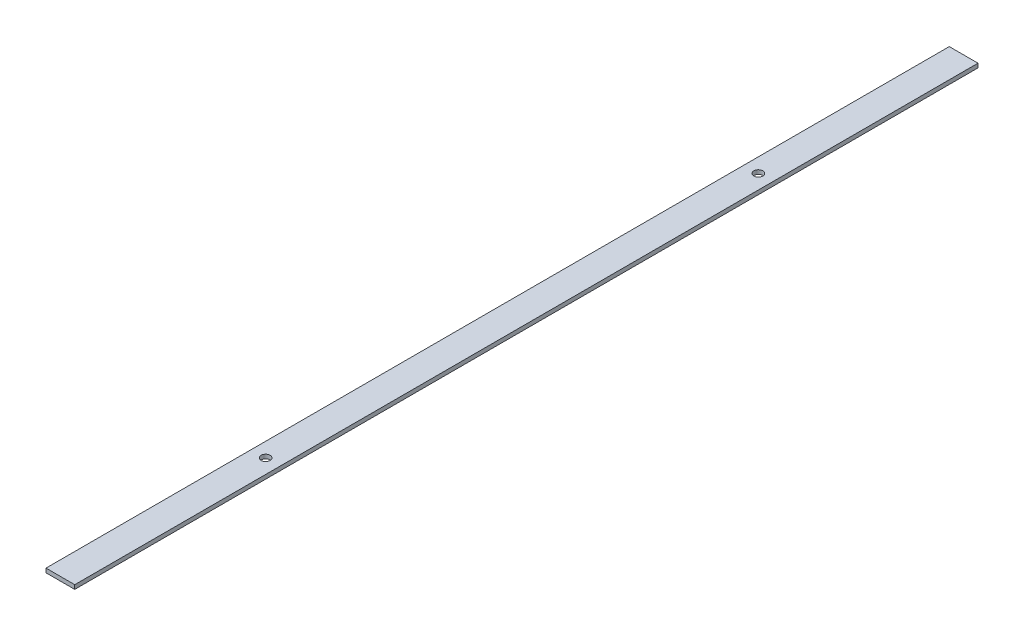
SolidWorks part; units mm, degrees
ref_plane "前视基准面" through (0, 0, 0) normal (0, 0, 1) x (1, 0, 0)
ref_plane "上视基准面" through (0, 0, 0) normal (0, 1, 0) x (1, 0, 0)
ref_plane "右视基准面" through (0, 0, 0) normal (1, 0, 0) x (0, 0, -1)
sketch "草图1" plane through (0, 0, 0) normal (0, 0, 1) x (1, 0, 0)
  line L1 (0, 0) -> (70, 0)
  line L2 (0, 0) -> (0, 10)
  line L3 (0, 10) -> (70, 10)
  line L4 (70, 0) -> (70, 10)
  dimension "D1" = 70
  dimension "D2" = 10
extrude "凸台-拉伸1" add sketch "草图1" against normal blind 2200
sketch "草图2" plane through (0, 10, 0) normal (0, 1, 0) x (1, 0, 0)
  line L0 (-930, 1100) -> (49070, 1100) construction
  line L1 (70, 2200) -> (70, 0) construction
  line L2 (35, 1200) -> (35, 51200) construction
  line L3 (70, 2200) -> (0, 2200) construction
  circle A0 centre (35, 1700) radius 11
  circle A1 centre (35, 500) radius 11
  point P5 (70, 1100)
  point P10 (35, 2200)
  dimension "D1" = 22
  dimension "D2" = 22
  dimension "D3" = 1200
extrude "切除-拉伸1" cut sketch "草图2" against normal through all
